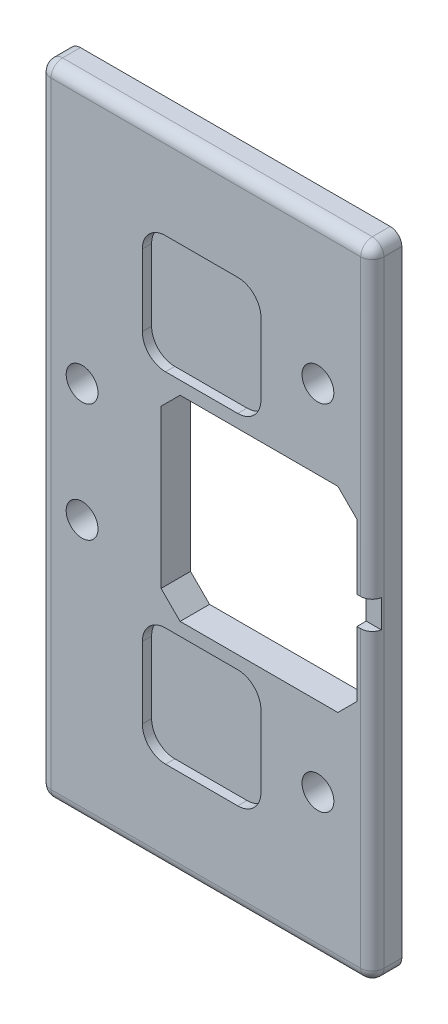
SolidWorks part; units mm, degrees
ref_plane "Front Plane" through (0, 0, 0) normal (0, 0, 1) x (1, 0, 0)
ref_plane "Top Plane" through (0, 0, 0) normal (0, 1, 0) x (1, 0, 0)
ref_plane "Right Plane" through (0, 0, 0) normal (1, 0, 0) x (0, 0, -1)
sketch "Sketch1" plane through (0, 0, 0) normal (0, 0, 1) x (1, 0, 0)
  line L0 (68.0566, 68.87) -> (126.0194, 68.87)
  line L22 (62.2146, 68.87) -> (68.0566, 68.87)
  line L28 (62.2146, -68.87) -> (126.0194, -68.87)
  line L31 (126.0194, -68.87) -> (126.0194, 68.87)
  line L38 (62.2146, 68.87) -> (54.2999, 68.87)
  line L40 (62.2146, -68.87) -> (54.2999, -68.87)
  line L41 (54.2999, 68.87) -> (54.2999, -68.87)
extrude "Boss-Extrude3" add sketch "Sketch1" along normal blind 6.35
ref_plane "Plane1" through (0, 0, 0) normal (0, -1, 0) x (-1, 0, 0)
sketch "Sketch6" plane through (0, 0, 0) normal (0, 0, -1) x (-1, 0, 0)
  circle A16 centre (-63.5, 12.7) radius 3.429
  circle A17 centre (-114.3, 38.1) radius 3.429
  circle A18 centre (-114.3, -38.1) radius 3.429
  circle A19 centre (-63.5, -12.7) radius 3.429
  dimension "D1" = 6.858
extrude "Cut-Extrude5" cut sketch "Sketch6" against normal up to surface (6.35 mm away) up to face at (90.1597, 0, 6.35)
fillet "Fillet2" radius 2.5 8 edges at (54.2999, 68.87, 3.175) (54.2999, -68.87, 3.175) (126.0194, -68.87, 3.175) (126.0194, 68.87, 3.175) (90.1597, 68.87, 6.35) (90.1597, -68.87, 6.35) (54.2999, 0, 6.35) (126.0194, 0, 6.35)
sketch "Sketch7" plane through (0, 0, 6.35) normal (0, 0, 1) x (1, 0, 0)
  line L0 (90.1597, -66.37) -> (90.1597, 66.37) construction
  line L3 (56.7999, -66.37) -> (123.5194, -66.37) construction
  line L5 (123.5194, 66.37) -> (56.7999, 66.37) construction
  line L6 (56.7999, 0) -> (123.5194, 0) construction
  line L7 (56.7999, 66.37) -> (56.7999, -66.37) construction
  line L8 (123.5194, -66.37) -> (123.5194, 66.37) construction
  circle A0 centre (90.1597, 0) radius 3.43
  dimension "D1" = 6.86
extrude "Cut-Extrude6" cut sketch "Sketch7" against normal through all
sketch "Sketch10" plane through (0, 0, 6.35) normal (0, 0, 1) x (1, 0, 0)
  line L0 (80.5121, 0) -> (56.7999, 0) construction
  line L14 (80.5121, 21.0947) -> (122.7015, 21.0947)
  line L15 (80.5121, 21.0947) -> (80.5121, -21.0947)
  line L16 (80.5121, -21.0947) -> (122.7015, -21.0947)
  line L17 (122.7015, 21.0947) -> (122.7015, -21.0947)
  line L18 (56.7999, 66.37) -> (56.7999, -66.37) construction
  dimension "D1" = 23.7122
extrude "Cut-Extrude8" cut sketch "Sketch10" against normal through all
sketch "Sketch11" plane through (0, 0, 6.35) normal (0, 0, 1) x (1, 0, 0)
  line L0 (123.5194, -66.37) -> (123.5194, 66.37) construction
  line L1 (123.5194, -3) -> (122.7015, -3)
  line L3 (123.5194, 3) -> (122.7015, 3)
  line L4 (122.7015, -3) -> (122.7015, 3)
  line L5 (122.7015, -21.0947) -> (122.7015, 21.0947) construction
  line L6 (123.1104, 3) -> (123.1104, 66.37) construction
  line L7 (123.5194, -3) -> (127.3985, -3)
  line L9 (123.5194, 3) -> (127.3985, 3)
  line L10 (127.3985, -3) -> (127.3985, 3)
  line L11 (123.5194, 66.37) -> (56.7999, 66.37) construction
  line L12 (123.1104, -3) -> (123.1104, -66.37) construction
  line L13 (56.7999, -66.37) -> (123.5194, -66.37) construction
  dimension "D1" = 6
extrude "Cut-Extrude9" cut sketch "Sketch11" against normal blind 2
sketch "Sketch12" plane through (0, 0, 6.35) normal (0, 0, 1) x (1, 0, 0)
  line L0 (76.4742, -44.3) -> (76.4742, -50.9707) construction
  line L1 (81.4742, -49.3) -> (76.4742, -49.3) construction
  line L2 (96.8742, -23.9) -> (102.0243, -23.9) construction
  line L3 (102.0243, -23.9) -> (101.8742, -28.9) construction
  line L5 (76.4742, -49.3) -> (102.0243, -49.3)
  line L6 (76.4742, -49.3) -> (76.4742, -23.9)
  line L7 (76.4742, -23.9) -> (102.0243, -23.9)
  line L8 (102.0243, -49.3) -> (102.0243, -23.9)
extrude "Cut-Extrude10" cut sketch "Sketch12" against normal blind 2
fillet "Fillet3" radius 5 4 edges at (102.0243, -23.9, 5.35) (76.4742, -23.9, 5.35) (76.4742, -49.3, 5.35) (102.0243, -49.3, 5.35)
mirror "Mirror1" about plane through (0, 0, 0) normal (0, -1, 0) of "Fillet3", "Cut-Extrude10"
chamfer "Chamfer1" distance 4.1 angle 45 4 edges at (80.5121, -21.0947, 3.175) (80.5121, 21.0947, 3.175) (122.7015, 21.0947, 3.175) (122.7015, -21.0947, 3.175)
